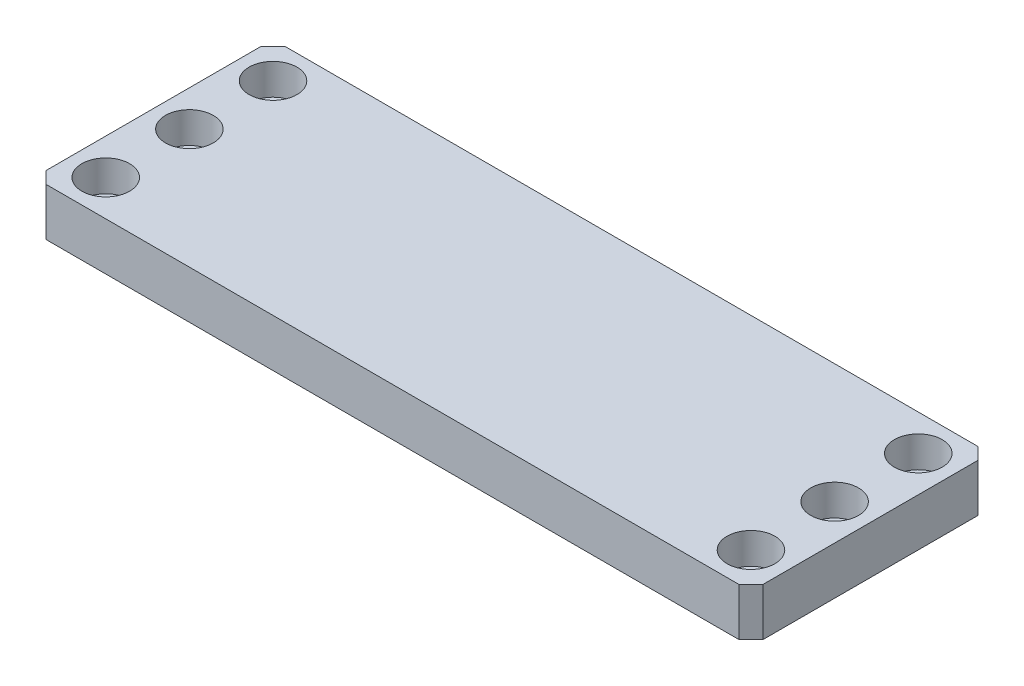
SolidWorks part; units mm, degrees
material "6061 Alloy"
ref_plane "Front Plane" through (0, 0, 0) normal (0, 0, 1) x (1, 0, 0)
ref_plane "Top Plane" through (0, 0, 0) normal (0, 1, 0) x (1, 0, 0)
ref_plane "Right Plane" through (0, 0, 0) normal (1, 0, 0) x (0, 0, -1)
sketch "Sketch1" plane through (0, 0, 0) normal (0, 1, 0) x (1, 0, 0)
  line L1 (150, -50) -> (-150, -50)
  line L2 (150, -50) -> (150, 50)
  line L3 (150, 50) -> (-150, 50)
  line L4 (-150, -50) -> (-150, 50)
  line L5 (150, -50) -> (-150, 50) construction
  line L6 (150, 50) -> (-150, -50) construction
  point P0 (0, 0)
  dimension "D1" = 100
  dimension "D2" = 300
extrude "Boss-Extrude1" add sketch "Sketch1" along normal blind 20
hole_wizard "CBORE for M12 Hexagon socket head cap screws1" positions "Sketch2" profile "Sketch3" counterbore size "M12" standard "GB" end condition through all
sketch "Sketch2" plane through (0, 20, 0) normal (0, 1, 0) x (1, 0, 0)
  line L0 (-135, 35) -> (-135, -35) construction
  line L1 (0, -11) -> (0, 11) construction
  line L2 (-150, 50) -> (-150, -50) construction
  point P5 (-135, 35)
  point P6 (-135, -35)
  point P9 (-135, 0)
  point P20 (135, 0)
  point P21 (135, -35)
  point P22 (135, 35)
  dimension "D1" = 70
  dimension "D2" = 15
sketch "Sketch3" plane through (-135, 20, -35) normal (1, 0, 0) x (0, 0, 1)
  line L0 (0, 0) -> (0, 20)
  line L1 (0, 20) -> (6.75, 20)
  line L3 (6.75, 20) -> (6.75, 13)
  line L4 (6.75, 13) -> (10, 13)
  line L5 (10, 13) -> (10, 0)
  line L7 (10, 0) -> (0, 0)
  line L11 (0, -6.35) -> (0, 107.95) construction
  dimension "Thru Hole Dia." = 13.5
  dimension "Thru Hole Depth" = 20
  dimension "C'Bore Dia." = 20
  dimension "C'Bore Depth" = 13
chamfer "Chamfer1" distance 5 angle 45 4 edges at (150, 10, -50) (150, 10, 50) (-150, 10, -50) (-150, 10, 50)
hole_wizard "M8 Tapped Hole1" positions "Sketch4" profile "Sketch6" tap size "M8" standard "GB"
sketch "Sketch4" plane through (0, 0, 0) normal (0, -1, 0) x (-1, 0, 0)
  line L0 (0, 11) -> (0, -11) construction
  line L1 (-11, 0) -> (11, 0) construction
  point P0 (-37.8, 37.8)
  point P5 (37.8, 37.8)
  point P8 (37.8, -37.8)
  point P9 (-37.8, -37.8)
  dimension "D1" = 75.6
  dimension "D2" = 75.6
sketch "Sketch6" plane through (37.8, 0, -37.8) normal (1, 0, 0) x (0, 0, -1)
  line L0 (0, 0) -> (0, 17.0429)
  line L1 (0, 17.0429) -> (3.4, 15)
  line L2 (3.4, 15) -> (3.4, 0)
  line L5 (3.4, 0) -> (0, 0)
  line L10 (0, 17.0429) -> (-3.4, 15) construction
  line L11 (0, -6.35) -> (0, 107.95) construction
  dimension "Tap Drill Dia." = 6.8
  dimension "Tap Drill Depth" = 15
  dimension "Drill Angle" = 118
cosmetic thread "Hole Thread1"
cosmetic thread "Hole Thread2"
cosmetic thread "Hole Thread3"
cosmetic thread "Hole Thread4"
